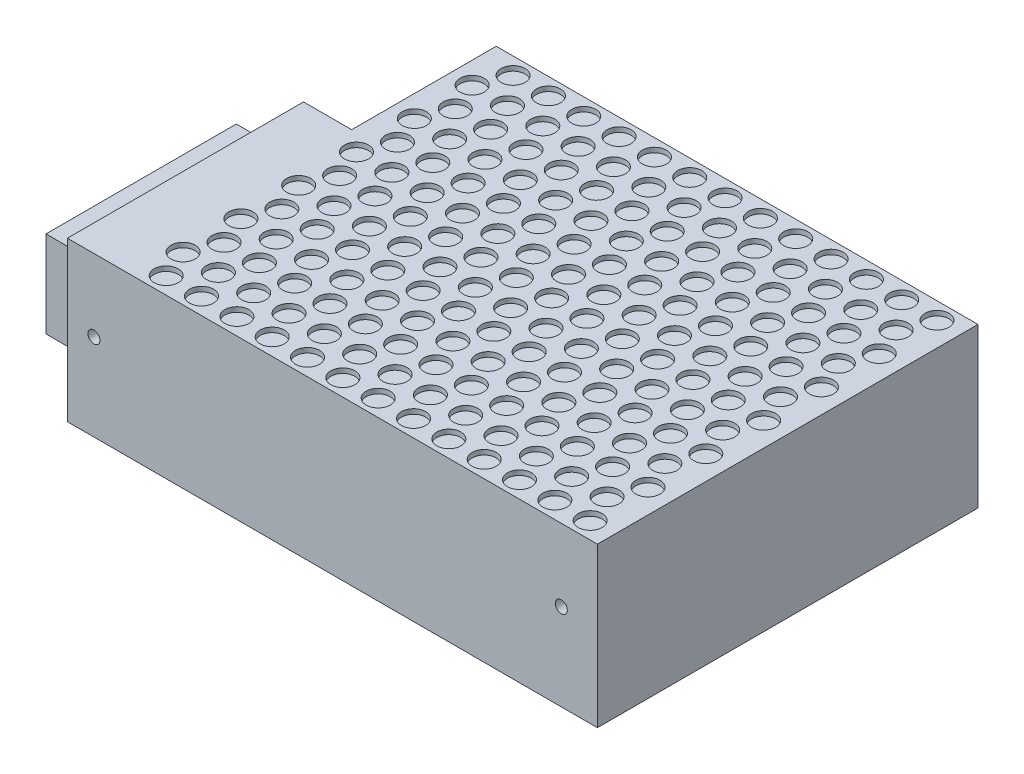
SolidWorks part; units mm, degrees
ref_plane "正面" through (0, 0, 0) normal (0, 0, 1) x (1, 0, 0)
ref_plane "平面" through (0, 0, 0) normal (0, 1, 0) x (1, 0, 0)
ref_plane "右側面" through (0, 0, 0) normal (1, 0, 0) x (0, 0, -1)
sketch "ｽｹｯﾁ1" plane through (0, 0, 0) normal (0, 1, 0) x (1, 0, 0)
  line L1 (-55, -39.5) -> (55, -39.5)
  line L2 (-55, -39.5) -> (-55, 39.5)
  line L3 (-55, 39.5) -> (55, 39.5)
  line L4 (55, -39.5) -> (55, 39.5)
  line L5 (-55, -39.5) -> (55, 39.5) construction
  line L6 (-55, 39.5) -> (55, -39.5) construction
  point P0 (0, 0)
  point P6 (49, -33.5)
  point P7 (-51, 34)
  dimension "D1" = 110
  dimension "D2" = 79
  dimension "D3" = 4
  dimension "D4" = 100
  dimension "D5" = 6
  dimension "D6" = 67.5
extrude "ﾎﾞｽ - 押し出し1" add sketch "ｽｹｯﾁ1" along normal blind 33
sketch "ｽｹｯﾁ2" plane through (0, 33, 0) normal (0, 1, 0) x (1, 0, 0)
  line L0 (55, -39.5) -> (55, 39.5) construction
  line L1 (-38, 0) -> (-38, 12) construction
  line L2 (-40.5, -6) -> (47.5, -6) construction
  line L3 (-40.5, -6) -> (-40.5, 6) construction
  line L4 (-38, 0) -> (-38, -12) construction
  line L5 (-38, 0) -> (50, 0) construction
  line L6 (-33.1667, -6) -> (-33.1667, -18) construction
  line L7 (-38, -12) -> (-38, 0) construction
  line L8 (-38, -24) -> (-38, -12) construction
  line L9 (-38, -36) -> (-38, -24) construction
  circle A0 centre (-38, 0) radius 2.5
  circle A1 centre (-30.6667, 0) radius 2.5
  circle A2 centre (-23.3333, 0) radius 2.5
  circle A3 centre (-16, 0) radius 2.5
  circle A4 centre (-8.6667, 0) radius 2.5
  circle A5 centre (-1.3333, 0) radius 2.5
  circle A6 centre (6, 0) radius 2.5
  circle A7 centre (13.3333, 0) radius 2.5
  circle A8 centre (20.6667, 0) radius 2.5
  circle A9 centre (28, 0) radius 2.5
  circle A10 centre (35.3333, 0) radius 2.5
  circle A11 centre (42.6667, 0) radius 2.5
  circle A12 centre (50, 0) radius 2.5
  circle A13 centre (-38, 12) radius 2.5
  circle A14 centre (-30.6667, 12) radius 2.5
  circle A15 centre (-23.3333, 12) radius 2.5
  circle A16 centre (-16, 12) radius 2.5
  circle A17 centre (-8.6667, 12) radius 2.5
  circle A18 centre (-1.3333, 12) radius 2.5
  circle A19 centre (6, 12) radius 2.5
  circle A20 centre (13.3333, 12) radius 2.5
  circle A21 centre (20.6667, 12) radius 2.5
  circle A22 centre (28, 12) radius 2.5
  circle A23 centre (35.3333, 12) radius 2.5
  circle A24 centre (42.6667, 12) radius 2.5
  circle A25 centre (50, 12) radius 2.5
  circle A26 centre (-38, 24) radius 2.5
  circle A27 centre (-30.6667, 24) radius 2.5
  circle A28 centre (-23.3333, 24) radius 2.5
  circle A29 centre (-16, 24) radius 2.5
  circle A30 centre (-8.6667, 24) radius 2.5
  circle A31 centre (-1.3333, 24) radius 2.5
  circle A32 centre (6, 24) radius 2.5
  circle A33 centre (13.3333, 24) radius 2.5
  circle A34 centre (20.6667, 24) radius 2.5
  circle A35 centre (28, 24) radius 2.5
  circle A36 centre (35.3333, 24) radius 2.5
  circle A37 centre (42.6667, 24) radius 2.5
  circle A38 centre (50, 24) radius 2.5
  circle A39 centre (-38, -12) radius 2.5
  circle A40 centre (-30.6667, -12) radius 2.5
  circle A41 centre (-23.3333, -12) radius 2.5
  circle A42 centre (-16, -12) radius 2.5
  circle A43 centre (-8.6667, -12) radius 2.5
  circle A44 centre (-1.3333, -12) radius 2.5
  circle A45 centre (6, -12) radius 2.5
  circle A46 centre (13.3333, -12) radius 2.5
  circle A47 centre (20.6667, -12) radius 2.5
  circle A48 centre (28, -12) radius 2.5
  circle A49 centre (35.3333, -12) radius 2.5
  circle A50 centre (42.6667, -12) radius 2.5
  circle A51 centre (50, -12) radius 2.5
  circle A52 centre (-38, -24) radius 2.5
  circle A53 centre (-30.6667, -24) radius 2.5
  circle A54 centre (-23.3333, -24) radius 2.5
  circle A55 centre (-16, -24) radius 2.5
  circle A56 centre (-8.6667, -24) radius 2.5
  circle A57 centre (-1.3333, -24) radius 2.5
  circle A58 centre (6, -24) radius 2.5
  circle A59 centre (13.3333, -24) radius 2.5
  circle A60 centre (20.6667, -24) radius 2.5
  circle A61 centre (28, -24) radius 2.5
  circle A62 centre (35.3333, -24) radius 2.5
  circle A63 centre (42.6667, -24) radius 2.5
  circle A64 centre (50, -24) radius 2.5
  circle A65 centre (-40.5, -6) radius 2.5
  circle A66 centre (-33.1667, -6) radius 2.5
  circle A67 centre (-25.8333, -6) radius 2.5
  circle A68 centre (-18.5, -6) radius 2.5
  circle A69 centre (-11.1667, -6) radius 2.5
  circle A70 centre (-3.8333, -6) radius 2.5
  circle A71 centre (3.5, -6) radius 2.5
  circle A72 centre (10.8333, -6) radius 2.5
  circle A73 centre (18.1667, -6) radius 2.5
  circle A74 centre (25.5, -6) radius 2.5
  circle A75 centre (32.8333, -6) radius 2.5
  circle A76 centre (40.1667, -6) radius 2.5
  circle A77 centre (47.5, -6) radius 2.5
  circle A78 centre (-40.5, 6) radius 2.5
  circle A79 centre (-33.1667, 6) radius 2.5
  circle A80 centre (-25.8333, 6) radius 2.5
  circle A81 centre (-18.5, 6) radius 2.5
  circle A82 centre (-11.1667, 6) radius 2.5
  circle A83 centre (-3.8333, 6) radius 2.5
  circle A84 centre (3.5, 6) radius 2.5
  circle A85 centre (10.8333, 6) radius 2.5
  circle A86 centre (18.1667, 6) radius 2.5
  circle A87 centre (25.5, 6) radius 2.5
  circle A88 centre (32.8333, 6) radius 2.5
  circle A89 centre (40.1667, 6) radius 2.5
  circle A90 centre (47.5, 6) radius 2.5
  circle A91 centre (-40.5, 18) radius 2.5
  circle A92 centre (-33.1667, 18) radius 2.5
  circle A93 centre (-25.8333, 18) radius 2.5
  circle A94 centre (-18.5, 18) radius 2.5
  circle A95 centre (-11.1667, 18) radius 2.5
  circle A96 centre (-3.8333, 18) radius 2.5
  circle A97 centre (3.5, 18) radius 2.5
  circle A98 centre (10.8333, 18) radius 2.5
  circle A99 centre (18.1667, 18) radius 2.5
  circle A100 centre (25.5, 18) radius 2.5
  circle A101 centre (32.8333, 18) radius 2.5
  circle A102 centre (40.1667, 18) radius 2.5
  circle A103 centre (47.5, 18) radius 2.5
  circle A104 centre (-40.5, 30) radius 2.5
  circle A105 centre (-33.1667, 30) radius 2.5
  circle A106 centre (-25.8333, 30) radius 2.5
  circle A107 centre (-18.5, 30) radius 2.5
  circle A108 centre (-11.1667, 30) radius 2.5
  circle A109 centre (-3.8333, 30) radius 2.5
  circle A110 centre (3.5, 30) radius 2.5
  circle A111 centre (10.8333, 30) radius 2.5
  circle A112 centre (18.1667, 30) radius 2.5
  circle A113 centre (25.5, 30) radius 2.5
  circle A114 centre (32.8333, 30) radius 2.5
  circle A115 centre (40.1667, 30) radius 2.5
  circle A116 centre (47.5, 30) radius 2.5
  circle A117 centre (-33.1667, -18) radius 2.5
  circle A118 centre (-25.8333, -18) radius 2.5
  circle A119 centre (-18.5, -18) radius 2.5
  circle A120 centre (-11.1667, -18) radius 2.5
  circle A121 centre (-3.8333, -18) radius 2.5
  circle A122 centre (3.5, -18) radius 2.5
  circle A123 centre (10.8333, -18) radius 2.5
  circle A124 centre (18.1667, -18) radius 2.5
  circle A125 centre (25.5, -18) radius 2.5
  circle A126 centre (32.8333, -18) radius 2.5
  circle A127 centre (40.1667, -18) radius 2.5
  circle A128 centre (47.5, -18) radius 2.5
  circle A129 centre (-40.5, -18) radius 2.5
  circle A130 centre (-33.1667, -30) radius 2.5
  circle A131 centre (-25.8333, -30) radius 2.5
  circle A132 centre (-18.5, -30) radius 2.5
  circle A133 centre (-11.1667, -30) radius 2.5
  circle A134 centre (-3.8333, -30) radius 2.5
  circle A135 centre (3.5, -30) radius 2.5
  circle A136 centre (10.8333, -30) radius 2.5
  circle A137 centre (18.1667, -30) radius 2.5
  circle A138 centre (25.5, -30) radius 2.5
  circle A139 centre (32.8333, -30) radius 2.5
  circle A140 centre (40.1667, -30) radius 2.5
  circle A141 centre (47.5, -30) radius 2.5
  circle A142 centre (-40.5, -30) radius 2.5
  circle A143 centre (-38, 36) radius 2.5
  circle A144 centre (-30.6667, 36) radius 2.5
  circle A145 centre (-23.3333, 36) radius 2.5
  circle A146 centre (-16, 36) radius 2.5
  circle A147 centre (-8.6667, 36) radius 2.5
  circle A148 centre (-1.3333, 36) radius 2.5
  circle A149 centre (6, 36) radius 2.5
  circle A150 centre (13.3333, 36) radius 2.5
  circle A151 centre (20.6667, 36) radius 2.5
  circle A152 centre (28, 36) radius 2.5
  circle A153 centre (35.3333, 36) radius 2.5
  circle A154 centre (42.6667, 36) radius 2.5
  circle A155 centre (50, 36) radius 2.5
  circle A156 centre (-38, -36) radius 2.5
  circle A157 centre (-30.6667, -36) radius 2.5
  circle A158 centre (-23.3333, -36) radius 2.5
  circle A159 centre (-16, -36) radius 2.5
  circle A160 centre (-8.6667, -36) radius 2.5
  circle A161 centre (-1.3333, -36) radius 2.5
  circle A162 centre (6, -36) radius 2.5
  circle A163 centre (13.3333, -36) radius 2.5
  circle A164 centre (20.6667, -36) radius 2.5
  circle A165 centre (28, -36) radius 2.5
  circle A166 centre (35.3333, -36) radius 2.5
  circle A167 centre (42.6667, -36) radius 2.5
  circle A168 centre (50, -36) radius 2.5
  dimension "D1" = 5
  dimension "D2" = 88
  dimension "D4" = 5
  dimension "D6" = 12
  dimension "D8" = 12
  dimension "D10" = 6
  dimension "D11" = 2.5
  dimension "D13" = 12
  dimension "D15" = 12
  dimension "D3" = 13
  dimension "D5" = 4
  dimension "D7" = 4
  dimension "D9" = 2
  dimension "D12" = 4
  dimension "D14" = 3
extrude "ｶｯﾄ - 押し出し1" cut sketch "ｽｹｯﾁ2" against normal blind 1
sketch "ｽｹｯﾁ3" plane through (0, 0, -39.5) normal (0, 0, -1) x (-1, 0, 0)
  line L0 (-55, 33) -> (55, 33) construction
  line L3 (-47.5, 16.5) -> (-47.5, 28.5) construction
  line L4 (-47.5, 16.5) -> (40.5, 16.5) construction
  line L5 (38, 33) -> (-50, 33) construction
  line L6 (-47.5, 16.5) -> (-47.5, 4.5) construction
  line L7 (-50, 10.5) -> (38, 10.5) construction
  line L8 (-55, 33) -> (-55, 0) construction
  line L9 (-50, 10.5) -> (-50, 22.5) construction
  circle A0 centre (-47.5, 16.5) radius 2.5
  circle A1 centre (-40.1667, 16.5) radius 2.5
  circle A2 centre (-32.8333, 16.5) radius 2.5
  circle A3 centre (-25.5, 16.5) radius 2.5
  circle A4 centre (-18.1667, 16.5) radius 2.5
  circle A5 centre (-10.8333, 16.5) radius 2.5
  circle A6 centre (-3.5, 16.5) radius 2.5
  circle A7 centre (3.8333, 16.5) radius 2.5
  circle A8 centre (11.1667, 16.5) radius 2.5
  circle A9 centre (18.5, 16.5) radius 2.5
  circle A10 centre (25.8333, 16.5) radius 2.5
  circle A11 centre (33.1667, 16.5) radius 2.5
  circle A12 centre (40.5, 16.5) radius 2.5
  circle A13 centre (-47.5, 28.5) radius 2.5
  circle A14 centre (-40.1667, 28.5) radius 2.5
  circle A15 centre (-32.8333, 28.5) radius 2.5
  circle A16 centre (-25.5, 28.5) radius 2.5
  circle A17 centre (-18.1667, 28.5) radius 2.5
  circle A18 centre (-10.8333, 28.5) radius 2.5
  circle A19 centre (-3.5, 28.5) radius 2.5
  circle A20 centre (3.8333, 28.5) radius 2.5
  circle A21 centre (11.1667, 28.5) radius 2.5
  circle A22 centre (18.5, 28.5) radius 2.5
  circle A23 centre (25.8333, 28.5) radius 2.5
  circle A24 centre (33.1667, 28.5) radius 2.5
  circle A25 centre (40.5, 28.5) radius 2.5
  circle A26 centre (-47.5, 4.5) radius 2.5
  circle A27 centre (-40.1667, 4.5) radius 2.5
  circle A28 centre (-32.8333, 4.5) radius 2.5
  circle A29 centre (-25.5, 4.5) radius 2.5
  circle A30 centre (-18.1667, 4.5) radius 2.5
  circle A31 centre (-10.8333, 4.5) radius 2.5
  circle A32 centre (-3.5, 4.5) radius 2.5
  circle A33 centre (3.8333, 4.5) radius 2.5
  circle A34 centre (11.1667, 4.5) radius 2.5
  circle A35 centre (18.5, 4.5) radius 2.5
  circle A36 centre (25.8333, 4.5) radius 2.5
  circle A37 centre (33.1667, 4.5) radius 2.5
  circle A38 centre (40.5, 4.5) radius 2.5
  circle A39 centre (-50, 10.5) radius 2.5
  circle A40 centre (-42.6667, 10.5) radius 2.5
  circle A41 centre (-35.3333, 10.5) radius 2.5
  circle A42 centre (-28, 10.5) radius 2.5
  circle A43 centre (-20.6667, 10.5) radius 2.5
  circle A44 centre (-13.3333, 10.5) radius 2.5
  circle A45 centre (-6, 10.5) radius 2.5
  circle A46 centre (1.3333, 10.5) radius 2.5
  circle A47 centre (8.6667, 10.5) radius 2.5
  circle A48 centre (16, 10.5) radius 2.5
  circle A49 centre (23.3333, 10.5) radius 2.5
  circle A50 centre (30.6667, 10.5) radius 2.5
  circle A51 centre (38, 10.5) radius 2.5
  circle A52 centre (-50, 22.5) radius 2.5
  circle A53 centre (-42.6667, 22.5) radius 2.5
  circle A54 centre (-35.3333, 22.5) radius 2.5
  circle A55 centre (-28, 22.5) radius 2.5
  circle A56 centre (-20.6667, 22.5) radius 2.5
  circle A57 centre (-13.3333, 22.5) radius 2.5
  circle A58 centre (-6, 22.5) radius 2.5
  circle A59 centre (1.3333, 22.5) radius 2.5
  circle A60 centre (8.6667, 22.5) radius 2.5
  circle A61 centre (16, 22.5) radius 2.5
  circle A62 centre (23.3333, 22.5) radius 2.5
  circle A63 centre (30.6667, 22.5) radius 2.5
  circle A64 centre (38, 22.5) radius 2.5
  dimension "D6" = 12
  dimension "D8" = 12
  dimension "D10" = 6
  dimension "D11" = 2.5
  dimension "D13" = 12
  dimension "D9" = 2
  dimension "D3" = 5
  dimension "D1" = 16.5
  dimension "D2" = 5
  dimension "D4" = 13
  dimension "D5" = 2
  dimension "D7" = 2
  dimension "D12" = 2
extrude "ｶｯﾄ - 押し出し2" cut sketch "ｽｹｯﾁ3" against normal blind 1
sketch "ｽｹｯﾁ4" plane through (0, 33, 0) normal (0, 1, 0) x (1, 0, 0)
  line L1 (-55, 39.5) -> (-45, 39.5)
  line L2 (-55, 39.5) -> (-55, 9.5)
  line L3 (-55, 9.5) -> (-45, 9.5)
  line L4 (-45, 39.5) -> (-45, 9.5)
  dimension "D1" = 10
  dimension "D2" = 30
extrude "ｶｯﾄ - 押し出し3" cut sketch "ｽｹｯﾁ4" against normal offset from surface (25 mm away) 8 up to face at (0, 0, 0)
hole_wizard "M3x0.5 ねじ穴1" positions "ｽｹｯﾁ6" profile "ｽｹｯﾁ5" tap size "M3x0.5" standard "JIS"
sketch "ｽｹｯﾁ6" plane through (0, 0, 0) normal (0, -1, 0) x (-1, 0, 0)
  point P0 (51, 34)
  point P3 (-49, -33.5)
sketch "ｽｹｯﾁ5" plane through (-51, 0, -34) normal (1, 0, 0) x (0, 0, -1)
  line L0 (0, 0) -> (0, 11.2511)
  line L1 (0, 11.2511) -> (1.25, 10.5)
  line L2 (1.25, 10.5) -> (1.25, 0)
  line L5 (1.25, 0) -> (0, 0)
  line L10 (0, 11.2511) -> (-1.25, 10.5) construction
  line L11 (0, -6.35) -> (0, 107.95) construction
  dimension "ねじ下穴ﾄﾞﾘﾙ直径" = 2.5
  dimension "ねじ下穴ﾄﾞﾘﾙの深さ" = 10.5
  dimension "ﾄﾞﾘﾙ角度" = 118
cosmetic thread "穴のねじ山1" parameters "D1"=8, "D2"=3
cosmetic thread "穴のねじ山2" parameters "D1"=8, "D2"=3
sketch "ｽｹｯﾁ7" plane through (-55, 0, 0) normal (-1, 0, 0) x (0, 0, 1)
  line L0 (-39.5, 0) -> (39.5, 0) construction
  line L1 (-7.55, 24) -> (31.95, 24)
  line L2 (-7.55, 24) -> (-7.55, 6)
  line L3 (-7.55, 6) -> (31.95, 6)
  line L4 (31.95, 24) -> (31.95, 6)
  line L5 (0.35, 24) -> (0.35, 6) construction
  line L6 (8.25, 24) -> (8.25, 6) construction
  line L7 (16.15, 24) -> (16.15, 6) construction
  line L8 (24.05, 24) -> (24.05, 6) construction
  line L9 (24.05, 15) -> (31.95, 15) construction
  line L10 (39.5, 33) -> (39.5, 0) construction
  point P4 (31.95, 15)
  point P17 (28, 15)
  dimension "D1" = 18
  dimension "D2" = 39.5
  dimension "D3" = 15
  dimension "D5" = 7.9
  dimension "D6" = 7.9
  dimension "D7" = 11.5
  dimension "D4" = 4
extrude "ﾎﾞｽ - 押し出し2" add sketch "ｽｹｯﾁ7" along normal blind 12
hole_wizard "M3x0.5 ねじ穴2" positions "ｽｹｯﾁ8" profile "ｽｹｯﾁ9" tap size "M3x0.5" standard "JIS"
sketch "ｽｹｯﾁ8" plane through (0, 0, 39.5) normal (0, 0, 1) x (1, 0, 0)
  line L0 (-49.5, 18) -> (47.5, 18) construction
  line L1 (-55, 0) -> (55, 0) construction
  line L2 (-55, 33) -> (-55, 0) construction
  point P0 (-49.5, 18)
  point P1 (47.5, 18)
  dimension "D1" = 97
  dimension "D2" = 18
  dimension "D3" = 5.5
sketch "ｽｹｯﾁ9" plane through (-49.5, 18, 39.5) normal (1, 0, 0) x (0, -1, 0)
  line L0 (0, 0) -> (0, 9.2511)
  line L1 (0, 9.2511) -> (1.25, 8.5)
  line L2 (1.25, 8.5) -> (1.25, 0)
  line L5 (1.25, 0) -> (0, 0)
  line L10 (0, 9.2511) -> (-1.25, 8.5) construction
  line L11 (0, -6.35) -> (0, 107.95) construction
  dimension "ねじ下穴ﾄﾞﾘﾙ直径" = 2.5
  dimension "ねじ下穴ﾄﾞﾘﾙの深さ" = 8.5
  dimension "ﾄﾞﾘﾙ角度" = 118
cosmetic thread "穴のねじ山3" parameters "D1"=6, "D2"=3
cosmetic thread "穴のねじ山4" parameters "D1"=6, "D2"=3
scale "Scale1" scale about origin uniform scaling yes scale factor 1
equation "\"D10@ｽｹｯﾁ2\"=\"D6@ｽｹｯﾁ2\"/2"
equation "\"D8@ｽｹｯﾁ2\"=\"D6@ｽｹｯﾁ2\""
equation "\"D13@ｽｹｯﾁ2\"=\"D6@ｽｹｯﾁ2\""
equation "\"D15@ｽｹｯﾁ2\"=\"D6@ｽｹｯﾁ2\""
equation "\"D1@ｽｹｯﾁ3\"=\"D1@ﾎﾞｽ - 押し出し1\"/2"
equation "\"D2@ｽｹｯﾁ3\"=\"D4@ｽｹｯﾁ2\""
equation "\"D3@ｽｹｯﾁ3\"=\"D1@ｽｹｯﾁ2\""
equation "\"D6@ｽｹｯﾁ3\"=\"D6@ｽｹｯﾁ2\""
equation "\"D8@ｽｹｯﾁ3\"=\"D6@ｽｹｯﾁ3\""
equation "\"D10@ｽｹｯﾁ3\"=\"D6@ｽｹｯﾁ3\"/2"
equation "\"D11@ｽｹｯﾁ3\"=\"D11@ｽｹｯﾁ2\""
equation "\"D13@ｽｹｯﾁ3\"=\"D6@ｽｹｯﾁ3\""
equation "\"D11@ｽｹｯﾁ2\"=\"D1@ｽｹｯﾁ2\"/2"
equation "\"D5@ｽｹｯﾁ7\"=\"D2@ｽｹｯﾁ7\"/5"
equation "\"D6@ｽｹｯﾁ7\"=\"D5@ｽｹｯﾁ7\""
